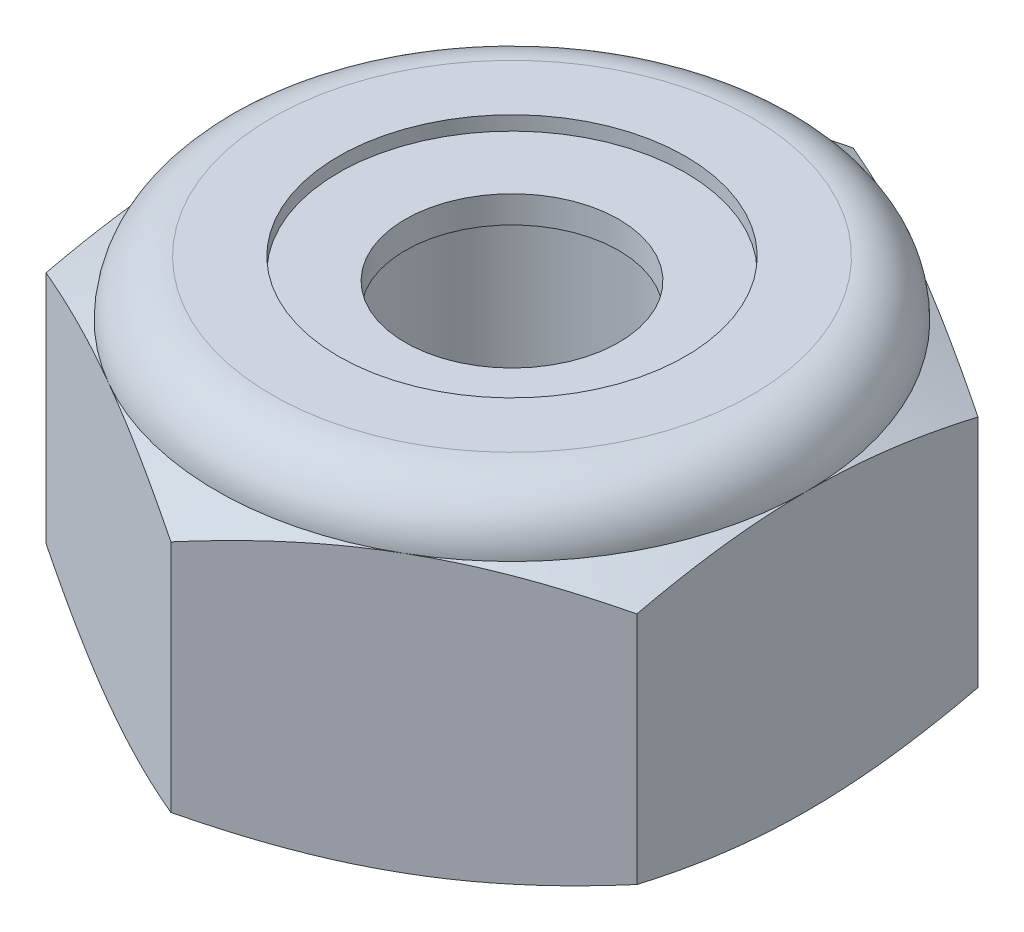
SolidWorks part; units mm, degrees
material "Alloy Steel"
ref_plane "Front" through (0, 0, 0) normal (0, 0, 1) x (1, 0, 0)
ref_plane "Top" through (0, 0, 0) normal (0, 1, 0) x (1, 0, 0)
ref_plane "Right" through (0, 0, 0) normal (1, 0, 0) x (0, 0, -1)
sketch "Sketch1" plane through (0, 0, 0) normal (0, 1, 0) x (1, 0, 0)
  line L1 (0, 3.6662) -> (-3.175, 1.8331)
  line L2 (-3.175, 1.8331) -> (-3.175, -1.8331)
  line L3 (-3.175, -1.8331) -> (0, -3.6662)
  line L4 (0, -3.6662) -> (3.175, -1.8331)
  line L5 (3.175, -1.8331) -> (3.175, 1.8331)
  line L6 (3.175, 1.8331) -> (0, 3.6662)
  circle A0 centre (0, 0) radius 3.175 construction
  dimension "Hex Flats" = 6.35
extrude "Extrude1" add sketch "Sketch1" along normal blind 3.5719
sketch "Sketch2" plane through (0, 0, 0) normal (1, 0, 0) x (0, 0, -1)
  line L0 (-1.4224, 0) -> (-1.4224, 3.5719) construction
  line L1 (0, 0) -> (1.4224, 0)
  line L2 (0, 0) -> (0, 3.5719)
  line L3 (0, 3.5719) -> (1.4224, 3.5719)
  line L4 (1.4224, 0) -> (1.4224, 3.5719)
  line L5 (-1.8331, 3.5719) -> (1.8331, 3.5719) construction
  line L7 (0, -1.4224) -> (0, 0) construction
  dimension "Thread Dia" = 2.8448
revolve "Revolve1" add sketch "Sketch2" angle 360 about L7
sketch "Sketch3" plane through (0, 0, 0) normal (1, 0, 0) x (0, 0, -1)
  line L0 (1.4224, 3.5719) -> (-1.4224, 3.5719) construction
  line L1 (-1.4224, 3.5719) -> (-1.4224, 2.9369) construction
  line L2 (-1.4224, 2.9369) -> (1.4224, 3.5719) construction
  line L3 (1.4224, 3.5719) -> (1.4397, 3.4944) construction
  line L4 (1.4397, 3.4944) -> (1.5607, 2.9521)
  line L5 (1.5607, 2.9521) -> (1.1821, 3.0709)
  line L6 (1.1821, 3.0709) -> (1.1475, 3.2259)
  line L7 (1.1475, 3.2259) -> (1.4397, 3.4944)
  line L8 (1.1648, 3.1484) -> (1.5002, 3.2233) construction
  line L9 (1.4224, 3.5719) -> (1.4224, 3.2059) construction
  line L10 (1.4224, 3.2059) -> (-1.4224, 2.5709) construction
  line L11 (-1.4224, 2.5709) -> (-1.4224, 2.9369) construction
  line L12 (-0.1526, 3.5719) -> (0.1526, 2.2049) construction
  line L13 (-1.4224, 0) -> (-1.4224, 3.5719) construction
  line L14 (0, 3.5719) -> (1.4224, 3.5719) construction
  line L15 (1.4224, 0) -> (1.4224, 3.5719) construction
  point P13 (0, 2.8884)
  dimension "D1" = 0.0794
  dimension "D2" = 0.1588
  dimension "Thread Pitch" = 0.635
  dimension "D4" = 60
  dimension "D5" = 0.635
revolve "Cut-Revolve1" [suppressed] cut sketch "Sketch3" angle 360 about L12
pattern_linear "LPattern1" [suppressed] count 6 spacing 0.635 along (0, 1, 0) count 2 spacing 0.635 along (0, 1, 0)
sketch "Sketch4" plane through (0, 0, 0) normal (1, 0, 0) x (0, 0, -1)
  line L0 (0, 3.5719) -> (1.4224, 3.5719)
  line L1 (1.4224, 3.5719) -> (1.1475, 3.4437)
  line L2 (1.1475, 3.4437) -> (1.1475, 0.1282)
  line L3 (1.1475, 0.1282) -> (1.4224, 0)
  line L4 (1.4224, 0) -> (0, 0)
  line L5 (0, 0) -> (0, 3.5719)
  line L6 (1.4224, 0) -> (1.4224, 3.5719) construction
  line L7 (0, 3.5719) -> (1.4224, 3.5719) construction
  line L8 (0, 0) -> (1.4224, 0) construction
  line L9 (0, 0) -> (0, 3.5719) construction
  line L10 (0, 3.5719) -> (0, 3.8752) construction
  dimension "D1" = 25
revolve "Cut-Revolve2" cut sketch "Sketch4" angle 360 about L10
combine bodies "Combine1" operation type subtract main body 112 bodies to subtract 109
sketch "Sketch5" plane through (0, 0, 0) normal (1, 0, 0) x (0, 0, -1)
  line L0 (0, 0) -> (3.175, 0)
  line L1 (3.175, 0) -> (3.6662, 0.229)
  line L2 (3.6662, 0.229) -> (3.6662, 2.7475)
  line L3 (3.6662, 2.7475) -> (3.175, 2.9766)
  line L4 (2.5797, 3.5719) -> (2.5797, 4.8419)
  line L5 (2.5797, 4.8419) -> (4.9362, 4.8419)
  line L6 (4.9362, 4.8419) -> (4.9362, -1.27)
  line L7 (4.9362, -1.27) -> (0, -1.27)
  line L8 (0, -1.27) -> (0, 0)
  line L9 (3.175, 2.9766) -> (3.175, 0) construction
  line L10 (0, 0) -> (1.4224, 0) construction
  line L13 (3.6662, 1.4883) -> (4.9362, 1.4883) construction
  line L14 (3.6662, 3.5719) -> (3.6662, 0) construction
  line L15 (0, 0) -> (0, 4.8419) construction
  line L20 (0, 4.8419) -> (2.5797, 4.8419) construction
  line L22 (0, 3.5719) -> (1.4224, 3.5719) construction
  arc A0 (3.175, 2.9766) -> (2.5797, 3.5719) centre (2.5797, 2.9766) ccw
  dimension "D1" = 25
  dimension "D2" = 1.27
  dimension "D3" = 3.5719
  dimension "D4" = 0.5953
revolve "Cut-Revolve3" cut sketch "Sketch5" angle 360 about L15
sketch "Sketch6" plane through (0, 0, 0) normal (1, 0, 0) x (0, 0, -1)
  line L0 (0, 2.9766) -> (3.0226, 2.9766)
  line L1 (2.5797, 3.4195) -> (1.8636, 3.4195)
  line L2 (0, 4.8419) -> (0, 2.9766)
  line L3 (1.8636, 4.8419) -> (0, 4.8419)
  line L4 (0, 4.8419) -> (2.5797, 4.8419) construction
  line L5 (0, 0) -> (0, 4.8419) construction
  line L6 (0, 4.8419) -> (0, 44.323) construction
  line L7 (1.8636, 3.4195) -> (1.8636, 4.8419)
  line L8 (2.5797, 3.5719) -> (2.5797, 3.4195) construction
  line L9 (1.8636, 3.4195) -> (1.1475, 3.4195) construction
  line L10 (1.1475, 3.4195) -> (1.1475, 3.4437) construction
  arc A0 (3.0226, 2.9766) -> (2.5797, 3.4195) centre (2.5797, 2.9766) ccw
  arc A1 (3.175, 2.9766) -> (2.5797, 3.5719) centre (2.5797, 2.9766) ccw construction
  dimension "D1" = 0.1524
revolve "Cut-Revolve4" cut sketch "Sketch6" angle 360 about L6
sketch "Sketch7" plane through (0, 0, 0) normal (1, 0, 0) x (0, 0, -1)
  line L0 (1.1475, 3.0528) -> (2.9384, 3.0528)
  line L1 (2.5797, 3.3433) -> (1.1475, 3.3433)
  line L2 (1.1475, 3.3433) -> (1.1475, 3.0528)
  line L3 (1.1475, 3.0528) -> (0, 3.0528) construction
  line L4 (0, 3.0528) -> (0, 3.3433) construction
  line L5 (0, 3.3433) -> (1.1475, 3.3433) construction
  line L6 (1.1475, 3.0528) -> (1.1475, 2.9766) construction
  line L7 (0, 2.9766) -> (3.0226, 2.9766) construction
  line L8 (2.5797, 3.3433) -> (2.5797, 3.4195) construction
  arc A0 (2.9384, 3.0528) -> (2.5797, 3.3433) centre (2.5797, 2.9766) ccw
  arc A2 (3.0226, 2.9766) -> (2.5797, 3.4195) centre (2.5797, 2.9766) ccw construction
  dimension "D1" = 0.0762
revolve "Revolve2" add sketch "Sketch7" angle 360 about L4
equation "\"D1@Sketch3\"=\"Thread Pitch@Sketch3\"/8"
equation "\"D2@Sketch3\"=\"Thread Pitch@Sketch3\"/4"
equation "\"D5@Sketch3\"=\"Thread Pitch@Sketch3\""
equation "\"D4@LPattern1\"=\"Thread Pitch@Sketch3\""
equation "\"D3@LPattern1\"=\"Thread Pitch@Sketch3\""
equation "\"D1@LPattern1\"=\"Height@Extrude1\"/\"Thread Pitch@Sketch3\""
equation "\"D4@Sketch5\"=\"Height@Extrude1\"/6"
